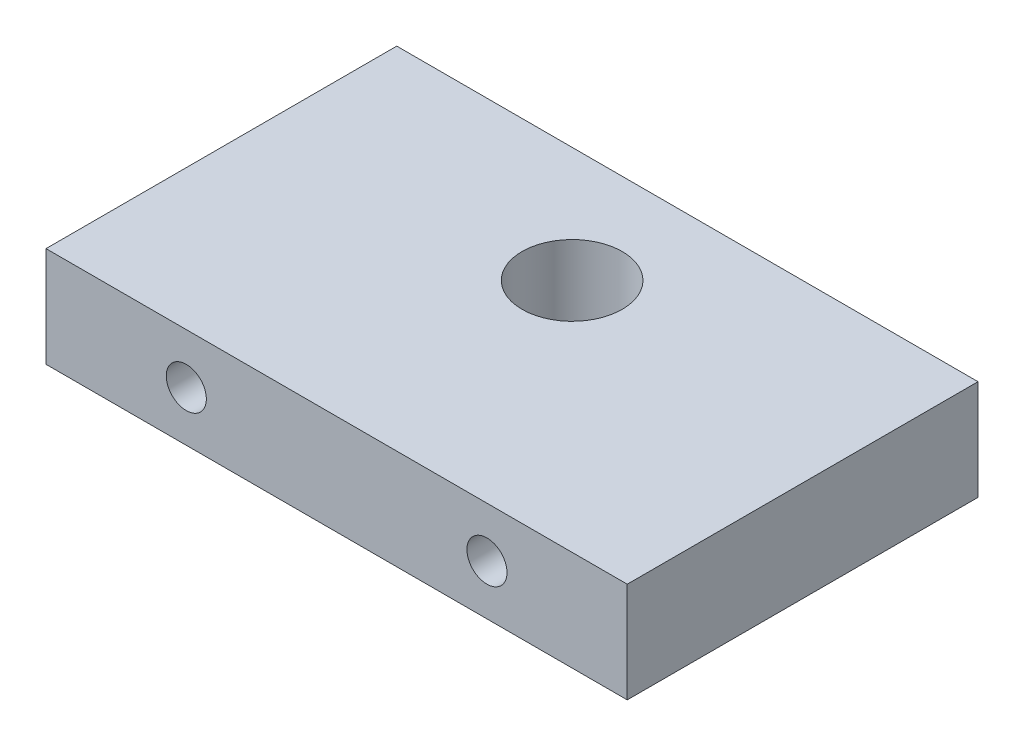
SolidWorks part; units mm, degrees
ref_plane "Front Plane" through (0, 0, 0) normal (0, 0, 1) x (1, 0, 0)
ref_plane "Top Plane" through (0, 0, 0) normal (0, 1, 0) x (1, 0, 0)
ref_plane "Right Plane" through (0, 0, 0) normal (1, 0, 0) x (0, 0, -1)
sketch "Sketch1" plane through (0, 0, 0) normal (0, 0, 1) x (1, 0, 0)
  line L1 (0, 0) -> (58, 0)
  line L2 (0, 0) -> (0, -10)
  line L3 (0, -10) -> (58, -10)
  line L4 (58, 0) -> (58, -10)
  circle A0 centre (14, -5) radius 2
  circle A1 centre (44, -5) radius 2
  dimension "D4" = 14
  dimension "D5" = 5
  dimension "D6" = 14
  dimension "D7" = 4
  dimension "D8" = 4
  dimension "D1" = 58
  dimension "D2" = 10
  dimension "D3" = 5
extrude "Boss-Extrude1" add sketch "Sketch1" along normal blind 45
sketch "Sketch3" plane through (0, 0, 0) normal (0, 0, -1) x (-1, 0, 0)
  line L4 (0, -10) -> (0, 0)
  line L5 (0, 0) -> (-58, 0)
  line L6 (-58, 0) -> (-58, -10)
  line L7 (-58, -10) -> (0, -10)
  line L8 (0, -10) -> (0, 0)
  line L9 (0, 0) -> (-58, 0)
  line L10 (-58, 0) -> (-58, -10)
  line L11 (-58, -10) -> (0, -10)
  dimension "D1" = 0
extrude "Cut-Extrude3" cut sketch "Sketch3" against normal blind 10
sketch "Sketch4" plane through (0, 0, 0) normal (0, 1, 0) x (1, 0, 0)
  line L0 (0, -10) -> (58, -10) construction
  circle A0 centre (29, -21.5) radius 5
  point P5 (29, -10)
  dimension "D1" = 10
  dimension "D2" = 11.5
extrude "Cut-Extrude4" cut sketch "Sketch4" against normal blind 10
